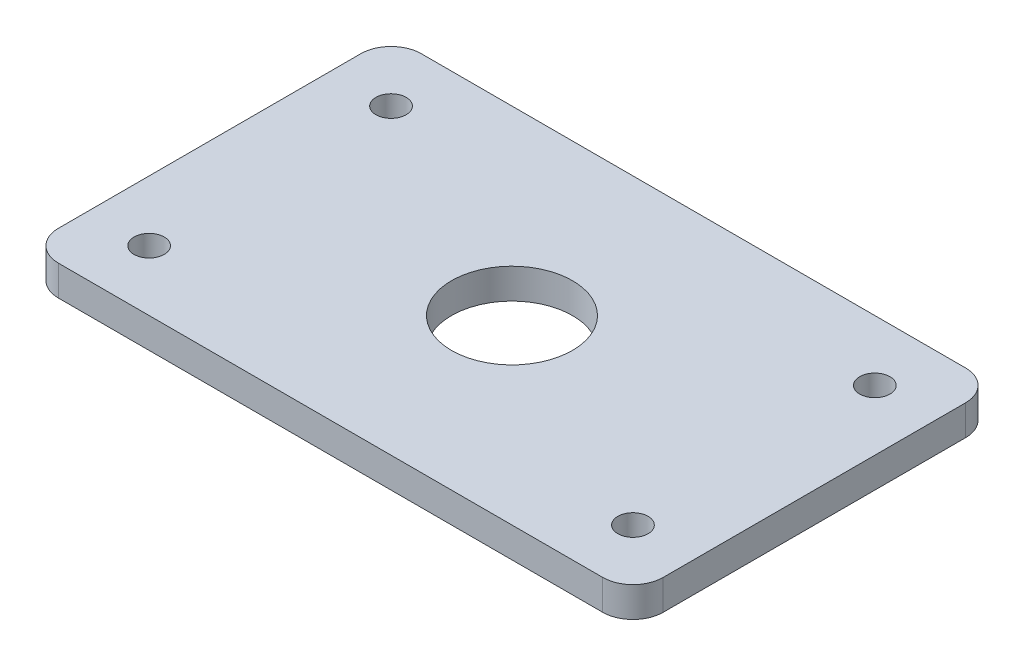
SolidWorks part; units mm, degrees
material "6061 Alloy"
ref_plane "Front Plane" through (0, 0, 0) normal (0, 0, 1) x (1, 0, 0)
ref_plane "Top Plane" through (0, 0, 0) normal (0, 1, 0) x (1, 0, 0)
ref_plane "Right Plane" through (0, 0, 0) normal (1, 0, 0) x (0, 0, -1)
sketch "Sketch1" plane through (0, 0, 0) normal (0, 1, 0) x (1, 0, 0)
  line L1 (63.5, -38.1) -> (-63.5, -38.1)
  line L2 (63.5, -38.1) -> (63.5, 38.1)
  line L3 (63.5, 38.1) -> (-63.5, 38.1)
  line L4 (-63.5, -38.1) -> (-63.5, 38.1)
  line L5 (63.5, -38.1) -> (-63.5, 38.1) construction
  line L6 (63.5, 38.1) -> (-63.5, -38.1) construction
  point P0 (0, 0)
  dimension "D1" = 127
  dimension "D2" = 76.2
extrude "Plate" add sketch "Sketch1" along normal blind 6.35
sketch "Sketch2" plane through (0, 6.35, 0) normal (0, 1, 0) x (1, 0, 0)
  line L0 (63.5, -38.1) -> (63.5, 38.1) construction
  line L1 (63.5, 38.1) -> (-63.5, 38.1) construction
  circle A0 centre (50.8, 25.4) radius 3.175
  dimension "D1" = 6.35
  dimension "D2" = 12.7
  dimension "D3" = 12.7
extrude "Cut-Extrude1" cut sketch "Sketch2" against normal through all
pattern_linear "LPattern1" count 2 spacing 101.6 along (-1, 0, 0) count 2 spacing 50.8 along (0, 0, 1) of "Cut-Extrude1"
sketch "Sketch4" plane through (0, 6.35, 0) normal (0, 1, 0) x (1, 0, 0)
  circle A0 centre (0, 0) radius 12.7
  dimension "D1" = 25.4
extrude "Cut-Extrude2" cut sketch "Sketch4" against normal through all
fillet "Fillet1" radius 6.35 4 edges at (63.5, 3.175, 38.1) (63.5, 3.175, -38.1) (-63.5, 3.175, -38.1) (-63.5, 3.175, 38.1)
